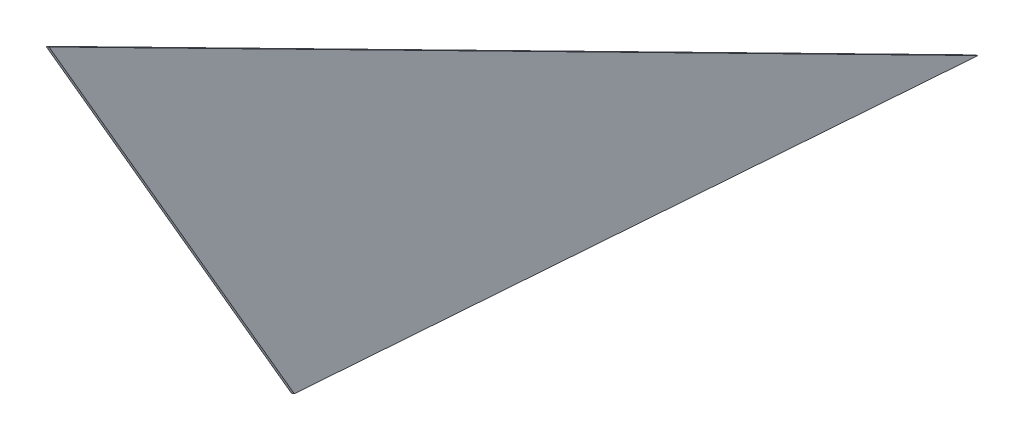
SolidWorks part; units mm, degrees
ref_plane "Front Plane" through (0, 0, 0) normal (0, 0, 1) x (1, 0, 0)
ref_plane "Top Plane" through (0, 0, 0) normal (0, 1, 0) x (1, 0, 0)
ref_plane "Right Plane" through (0, 0, 0) normal (1, 0, 0) x (0, 0, -1)
sketch "Sketch2" plane through (0, 0, 0) normal (0, 1, 0) x (1, 0, 0)
  line L4 (0, 0) -> (133.78, 581.4545) construction
  line L5 (133.78, 581.4545) -> (88.9, 0) construction
  line L6 (-70.9301, 0) -> (70.9301, 0) construction
  line L7 (88.9, 0) -> (0, 0) construction
  dimension "D1" = 88.9
  dimension "D2" = 583.184
  dimension "D3" = 596.646
sketch "Sketch3" plane through (0, 0, 0) normal (1, 0, 0) x (0, 0, -1)
  line L0 (0, 0) -> (-116.7037, 279.4) construction
  line L2 (0, 73.579) -> (0, -73.579) construction
  line L3 (73.579, 0) -> (-73.579, 0) construction
  point P3 (-24.1527, 252.8491)
  point P5 (0, 254)
  dimension "D1" = 279.4
  dimension "D2" = 22.67
ref_plane "Plane3" through (0, 0, 116.7037) normal (0, 0, 1) x (1, 0, 0)
sketch "Sketch7" plane through (0, 0, 116.7037) normal (0, 0, 1) x (1, 0, 0)
  line L0 (0, 279.4) -> (-19.05, 279.4) construction
  line L1 (0, 0) -> (0, 279.4) construction
  dimension "D1" = 19.05
ref_plane "Plane4" through (78.5779, 27.8263, 6.0651) normal (-0.9402, -0.3329, -0.0726) x (-0.0694, -0.0214, 0.9974)
sketch "Sketch8" plane through (78.5779, 27.8263, 6.0651) normal (-0.9402, -0.3329, -0.0726) x (-0.0694, -0.0214, 0.9974)
  line L0 (-589.018, -42.8808) -> (111.7377, 269.3996)
  line L1 (0, 0) -> (-589.2037, -42.8943) construction
  line L2 (111.7377, 269.3996) -> (-6.1699, -29.6575)
  line L3 (-6.1699, -29.6575) -> (-589.018, -42.8808)
extrude "Boss-Extrude2" add sketch "Sketch8" along normal blind 3.175
